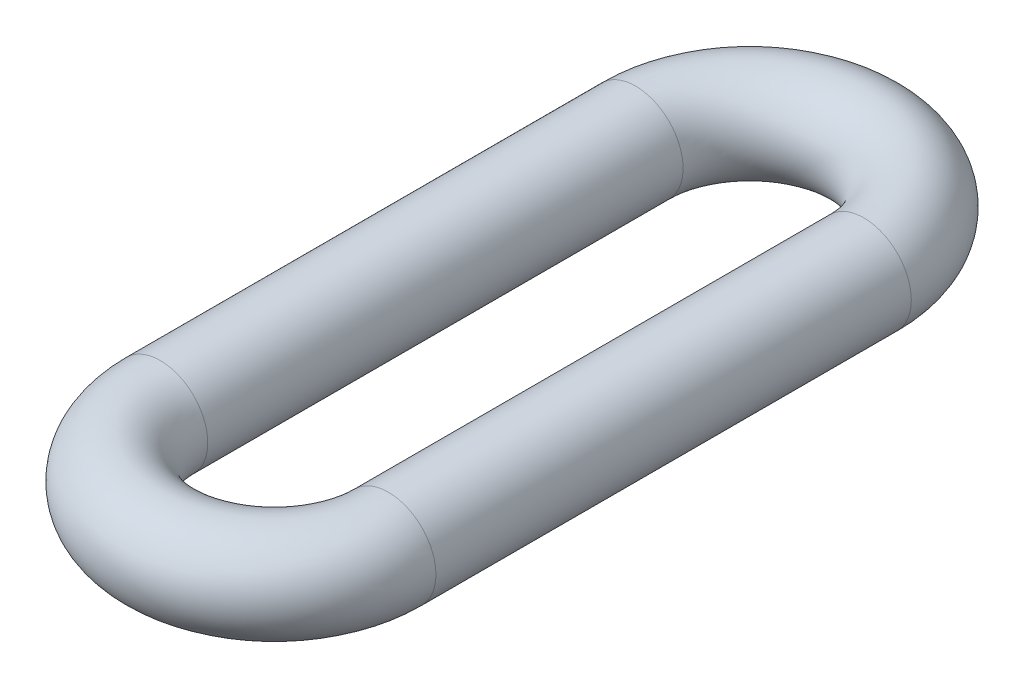
SolidWorks part; units mm, degrees
ref_plane "Front Plane" through (0, 0, 0) normal (0, 0, 1) x (1, 0, 0)
ref_plane "Top Plane" through (0, 0, 0) normal (0, 1, 0) x (1, 0, 0)
ref_plane "Right Plane" through (0, 0, 0) normal (1, 0, 0) x (0, 0, -1)
sketch "Sketch1" plane through (0, 0, 0) normal (0, 0, 1) x (1, 0, 0)
  circle A0 centre (0, 0) radius 50
  circle A1 centre (0, 0) radius 40
  dimension "D1" = 100
sketch "Sketch2" plane through (0, 0, 0) normal (0, 1, 0) x (1, 0, 0)
  line L0 (0, 0) -> (0, 500)
  line L1 (240, 500) -> (240, 0)
  arc A0 (0, 500) -> (240, 500) centre (120, 500) cw
  arc A1 (0, 0) -> (240, 0) centre (120, 0) ccw
  dimension "D2" = 120
  dimension "D1" = 500
sweep "Sweep1" add profiles "Sketch1" path "Sketch2"
